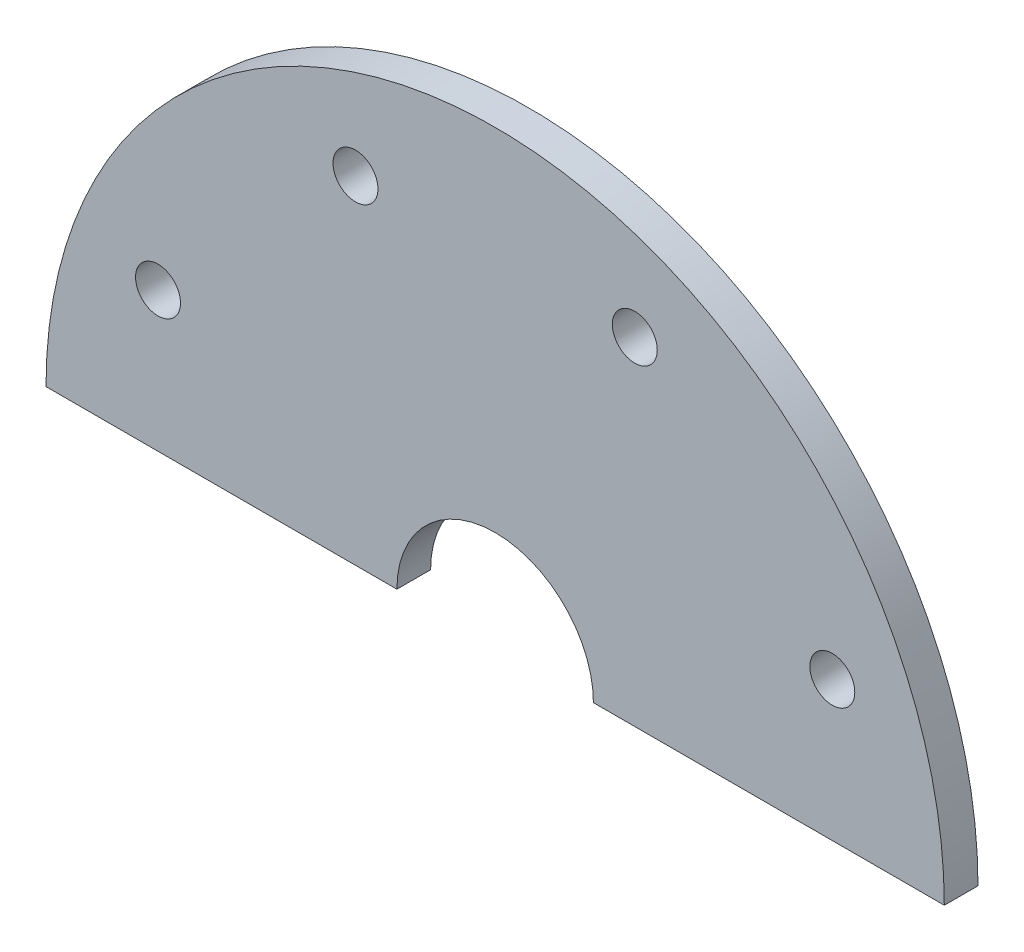
SolidWorks part; units mm, degrees
material "Plain Carbon Steel"
ref_plane "Front Plane" through (0, 0, 0) normal (0, 0, 1) x (1, 0, 0)
ref_plane "Top Plane" through (0, 0, 0) normal (0, 1, 0) x (1, 0, 0)
ref_plane "Right Plane" through (0, 0, 0) normal (1, 0, 0) x (0, 0, -1)
sketch "Sketch1" plane through (0, 0, 0) normal (0, 0, 1) x (1, 0, 0)
  line L0 (0, -55) -> (0, 55) construction
  line L3 (-80, 0) -> (-17.5, 0)
  line L5 (-60.0522, 24.8744) -> (0, 0) construction
  line L6 (0, 0) -> (60.0522, 24.8744) construction
  line L7 (55, 0) -> (-55, 0) construction
  line L8 (17.5, 0) -> (80, 0)
  line L9 (24.8744, 60.0522) -> (0, 0) construction
  arc A0 (17.5, 0) -> (-17.5, 0) centre (0, 0) ccw
  circle A1 centre (24.8744, 60.0522) radius 4
  circle A12 centre (60.0522, 24.8744) radius 4
  arc A15 (80, 0) -> (-80, 0) centre (0, 0) ccw
  circle A17 centre (-60.0522, 24.8744) radius 4
  circle A18 centre (-24.8744, 60.0522) radius 4
  point P0 (0, 0)
  point P26 (0, -19.4444)
  point P27 (0, 0)
  point P29 (0, 0)
  dimension "D1" = 22.5
  dimension "D4" = 8
  dimension "D7" = 80
  dimension "D8" = 17.5
  dimension "D2" = 22.5
  dimension "D3" = 65
  dimension "D5" = 65
  dimension "D6" = 65
  dimension "D9" = 22.5
extrude "Boss-Extrude1" add sketch "Sketch1" along normal blind 6
